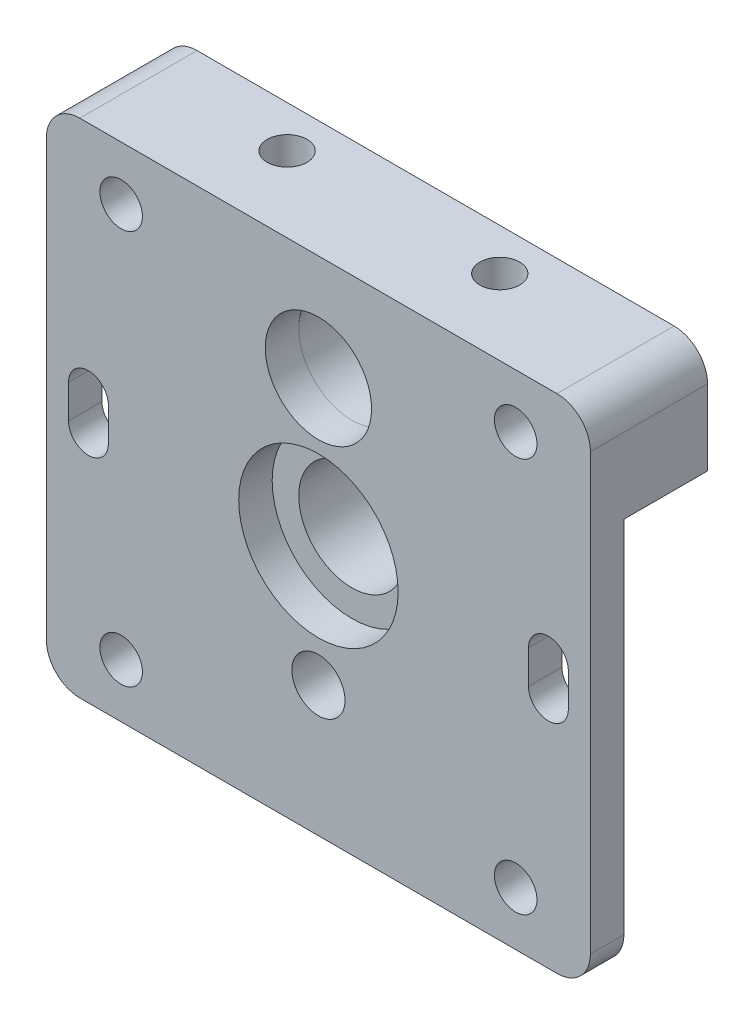
SolidWorks part; units mm, degrees
ref_plane "Front Plane" through (0, 0, 0) normal (0, 0, 1) x (1, 0, 0)
ref_plane "Top Plane" through (0, 0, 0) normal (0, 1, 0) x (1, 0, 0)
ref_plane "Right Plane" through (0, 0, 0) normal (1, 0, 0) x (0, 0, -1)
ref_plane "Plane1" through (10, 0, 0) normal (1, 0, 0) x (0, 0, -1)
sketch "Sketch2" plane through (10, 0, 0) normal (1, 0, 0) x (0, 0, -1)
  line L0 (-29.8625, -2) -> (-29.8625, 2)
  line L1 (0, 0) -> (-36.4992, 0) construction
  line L2 (23.5712, 23.5712) -> (-23.5712, 23.5712) construction
  line L3 (23.5712, 23.5712) -> (23.5712, -23.5712) construction
  line L4 (23.5712, -23.5712) -> (-23.5712, -23.5712) construction
  line L5 (-23.5712, 23.5712) -> (-23.5712, -23.5712) construction
  line L6 (23.5712, 23.5712) -> (-23.5712, -23.5712) construction
  line L7 (-28.5, 30) -> (28.5, 30)
  line L8 (-32.5, 26) -> (-32.5, -26)
  line L9 (-28.5, -30) -> (28.5, -30)
  line L10 (32.5, 26) -> (32.5, -26)
  line L13 (-25.1, -2) -> (-25.1, 2)
  line L14 (0, 0) -> (0, 18.4014) construction
  line L15 (25.1, -2) -> (25.1, 2)
  line L16 (29.8625, -2) -> (29.8625, 2)
  line L17 (23.5712, -23.5712) -> (-23.5712, 23.5712) construction
  circle A0 centre (23.5712, 23.5712) radius 2.54
  circle A1 centre (-23.5712, 23.5712) radius 2.54
  circle A2 centre (-23.5712, -23.5712) radius 2.54
  circle A3 centre (23.5712, -23.5712) radius 2.54
  circle A4 centre (0, 0) radius 9.525
  arc A5 (28.5, 30) -> (32.5, 26) centre (28.5, 26) cw
  arc A6 (-28.5, -30) -> (-32.5, -26) centre (-28.5, -26) cw
  arc A7 (28.5, -30) -> (32.5, -26) centre (28.5, -26) ccw
  arc A8 (-32.5, 26) -> (-28.5, 30) centre (-28.5, 26) cw
  circle A9 centre (0, 0) radius 27.4812 construction
  arc A10 (-29.8625, 2) -> (-25.1, 2) centre (-27.4812, 2) cw
  arc A11 (29.8625, -2) -> (25.1, -2) centre (27.4812, -2) cw
  arc A12 (-29.8625, -2) -> (-25.1, -2) centre (-27.4812, -2) ccw
  arc A13 (29.8625, 2) -> (25.1, 2) centre (27.4812, 2) ccw
  circle A14 centre (0, 0) radius 14.4156 construction
  circle A15 centre (0, 17.3355) radius 6.35
  circle A16 centre (0, -14.4156) radius 3.175
  point P0 (0, 0)
  point P10 (0, 0)
  dimension "D3" = 4
  dimension "D1" = 19.05
  dimension "D2" = 5.08
  dimension "D4" = 54.9625
  dimension "D6" = 28.8313
  dimension "D7" = 47.1424
  dimension "D5" = 2.3813
  dimension "D9" = 4
  dimension "D10" = 4
  dimension "D8" = 47.1424
sketch "Sketch3" plane through (0, 0, 0) normal (1, 0, 0) x (0, 0, -1)
  line L0 (19.7724, 15.4819) -> (11.2327, -18.9163)
  line L1 (-19.8282, 15.4871) -> (-11.1822, -18.9462)
  line L2 (-32.5, 17) -> (-32.5, 26)
  line L3 (28.5, 30) -> (-28.5, 30)
  line L4 (-32.5, 17) -> (-21.768, 17)
  line L5 (0, 0) -> (0, 32.3796) construction
  line L6 (32.5, 17) -> (32.5, 26)
  line L7 (32.5, 17) -> (21.7135, 17)
  line L9 (-23.5712, -23.5712) -> (23.5712, -23.5712) construction
  line L10 (-23.5712, -23.5712) -> (-23.5712, 23.5712) construction
  line L11 (-23.5712, 23.5712) -> (23.5712, 23.5712) construction
  line L12 (23.5712, -23.5712) -> (23.5712, 23.5712) construction
  line L13 (-23.5712, -23.5712) -> (23.5712, 23.5712) construction
  line L14 (-23.5712, 23.5712) -> (23.5712, -23.5712) construction
  arc A0 (-11.1822, -18.9462) -> (11.2327, -18.9163) centre (0, 0) ccw
  circle A1 centre (0, 0) radius 6.35
  arc A2 (21.7135, 17) -> (19.7724, 15.4819) centre (21.7135, 15) ccw
  arc A3 (-21.768, 17) -> (-19.8282, 15.4871) centre (-21.768, 15) cw
  circle A4 centre (0, 17.272) radius 6.35
  circle A6 centre (0, -14.4156) radius 3.175
  arc A7 (-32.5, 26) -> (-28.5, 30) centre (-28.5, 26) cw
  circle A8 centre (-23.5712, 23.5712) radius 2.54
  circle A9 centre (23.5712, 23.5712) radius 2.54
  arc A10 (32.5, 26) -> (28.5, 30) centre (28.5, 26) ccw
  point P38 (-6.35, 23.622)
  point P41 (6.35, 23.622)
  dimension "D1" = 12.7
  dimension "D3" = 47.1424
  dimension "D5" = 4
  dimension "D6" = 5.08
  dimension "D2" = 2
  dimension "D4" = 47.1424
  dimension "D7" = 4
extrude "Boss-Extrude1" add sketch "Sketch3" along normal blind 10
extrude "Boss-Extrude2" add sketch "Sketch2" along normal blind 4
ref_plane "Plane2" through (14, 0, 0) normal (1, 0, 0) x (0, 0, -1)
move or copy body "Body-Move/Copy1" bodies to move or copy 102 copy no rotation origin (7, 0, 0.02) rotation axis (0, 1, 0) rotation angle 180
ref_plane "Sketch5" through (0, 30, 0) normal (0, 1, 0) x (-1, 0, 0)
sketch "Sketch6" plane through (0, 30, 0) normal (0, 1, 0) x (-1, 0, 0)
  line L0 (0, 0) -> (-14, 0) construction
  line L1 (-14, 33) -> (-14, -33) construction
  line L4 (-8.9998, -12.7) -> (-9.0099, 12.7) construction
  circle A0 centre (-9.0049, 0) radius 12.7 construction
  circle A1 centre (-8.9998, -12.7) radius 2.3813
  circle A2 centre (-9.0099, 12.7) radius 2.3813
  dimension "D1" = 25.4
  dimension "D2" = 4.7625
extrude "Cut-Extrude1" cut sketch "Sketch6" against normal blind 60
move or copy body "Body-Move/Copy2" bodies to move or copy 106 copy no rotation origin (7, 0, 0.04) rotation axis (0, 1, 0) rotation angle 90
